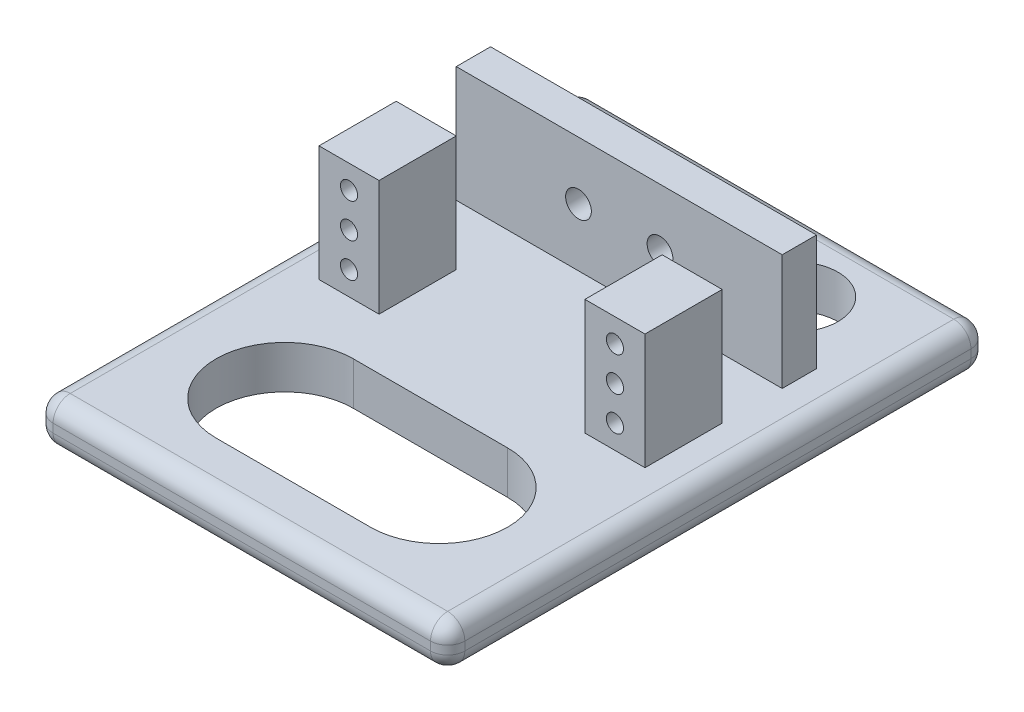
SolidWorks part; units mm, degrees
material "PET"
ref_plane "Alzado" through (0, 0, 0) normal (0, 0, 1) x (1, 0, 0)
ref_plane "Planta" through (0, 0, 0) normal (0, 1, 0) x (1, 0, 0)
ref_plane "Vista lateral" through (0, 0, 0) normal (1, 0, 0) x (0, 0, -1)
sketch "Croquis1" plane through (0, 0, 0) normal (0, 1, 0) x (1, 0, 0)
  line L0 (-9, -17.5) -> (9, -17.5) construction
  line L1 (-24, -31.5) -> (24, -31.5)
  line L2 (-24, -31.5) -> (-24, 31.5)
  line L3 (-24, 31.5) -> (24, 31.5)
  line L4 (24, -31.5) -> (24, 31.5)
  line L5 (-24, -31.5) -> (24, 31.5) construction
  line L6 (-24, 31.5) -> (24, -31.5) construction
  line L7 (-9, -9.5) -> (9, -9.5)
  line L8 (-9, -25.5) -> (9, -25.5)
  line L9 (-10.5, 22.5) -> (10.5, 22.5) construction
  arc A0 (-9, -9.5) -> (-9, -25.5) centre (-9, -17.5) ccw
  arc A1 (9, -25.5) -> (9, -9.5) centre (9, -17.5) ccw
  circle A2 centre (-10.5, 22.5) radius 5
  circle A3 centre (10.5, 22.5) radius 5
  point P0 (0, 0)
  point P8 (0, -17.5)
  point P17 (0, 22.5)
  dimension "D4" = 8
  dimension "D7" = 10
  dimension "D1" = 63
  dimension "D2" = 48
  dimension "D3" = 14
  dimension "D5" = 18
  dimension "D6" = 21
  dimension "D8" = 9
extrude "Saliente-Extruir1" add sketch "Croquis1" against normal blind 5
sketch "Croquis2" plane through (0, 0, 0) normal (0, 1, 0) x (1, 0, 0)
  line L0 (-24, -31.5) -> (24, -31.5) construction
  line L1 (12, 5.5) -> (19, 5.5)
  line L2 (12, 5.5) -> (12, -3.5)
  line L3 (12, -3.5) -> (19, -3.5)
  line L4 (19, 5.5) -> (19, -3.5)
  line L9 (0, -2.75) -> (0, 2.75) construction
  line L10 (-12, -3.5) -> (-19, -3.5)
  line L11 (-19, 5.5) -> (-19, -3.5)
  line L12 (-12, 5.5) -> (-19, 5.5)
  line L13 (-12, 5.5) -> (-12, -3.5)
  line L15 (19, 12.5) -> (-19, 12.5)
  line L16 (19, 12.5) -> (19, 16.5)
  line L17 (19, 16.5) -> (-19, 16.5)
  line L18 (-19, 12.5) -> (-19, 16.5)
  point P4 (15.5, -3.5)
  dimension "D1" = 7
  dimension "D2" = 9
  dimension "D3" = 15.5
  dimension "D4" = 28
  dimension "D5" = 38
  dimension "D6" = 4
  dimension "D7" = 7
extrude "Saliente-Extruir2" add sketch "Croquis2" along normal blind 13.5
sketch "Croquis3" plane through (0, 0, -12.5) normal (0, 0, 1) x (1, 0, 0)
  line L0 (19, 13.5) -> (19, 0) construction
  line L1 (-19, 13.5) -> (19, 13.5) construction
  line L2 (0, -10.175) -> (0, 10.175) construction
  circle A0 centre (4.75, 6.75) radius 1.5
  circle A1 centre (-4.75, 6.75) radius 1.5
  dimension "D1" = 3
  dimension "D2" = 14.25
  dimension "D3" = 6.75
extrude "Cortar-Extruir1" cut sketch "Croquis3" against normal up to next
sketch "Croquis4" plane through (0, 0, 3.5) normal (0, 0, 1) x (1, 0, 0)
  line L0 (12, 0) -> (19, 0) construction
  line L1 (19, 13.5) -> (19, 0) construction
  line L2 (19, 6.75) -> (12, 6.75) construction
  line L9 (12, 13.5) -> (12, 0) construction
  line L10 (0, -10.175) -> (0, 10.175) construction
  circle A0 centre (15.5, 6.75) radius 1
  circle A2 centre (15.5, 2.75) radius 1
  circle A7 centre (15.5, 10.75) radius 1
  circle A8 centre (-15.5, 2.75) radius 1
  circle A9 centre (-15.5, 6.75) radius 1
  circle A10 centre (-15.5, 10.75) radius 1
  point P11 (15.5, 6.75)
  point P13 (15.5, 6.75)
  point P19 (15.5, 6.75)
  dimension "D1" = 2
  dimension "D4" = 4
  dimension "D2" = 6.75
  dimension "D3" = 3.5
extrude "Cortar-Extruir2" cut sketch "Croquis4" against normal up to next
fillet "Redondeo1" radius 2 12 edges at (0, -5, -31.5) (0, 0, -31.5) (-24, -5, 0) (-24, -2.5, -31.5) (-24, 0, 0) (0, -5, 31.5) (-24, -2.5, 31.5) (0, 0, 31.5) (24, -2.5, -31.5) (24, -5, 0) (24, -2.5, 31.5) (24, 0, 0)
